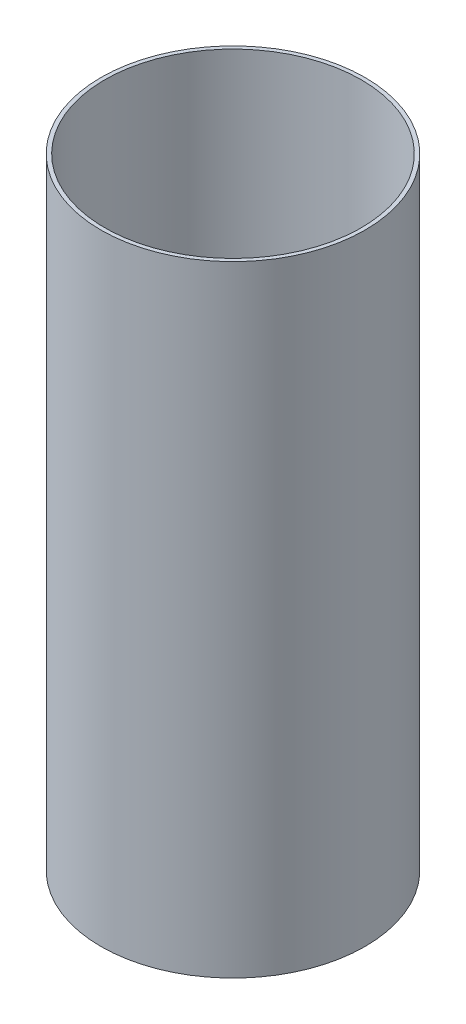
SolidWorks part; units mm, degrees
ref_plane "Front Plane" through (0, 0, 0) normal (0, 0, 1) x (1, 0, 0)
ref_plane "Top Plane" through (0, 0, 0) normal (0, 1, 0) x (1, 0, 0)
ref_plane "Right Plane" through (0, 0, 0) normal (1, 0, 0) x (0, 0, -1)
sketch "Sketch1" plane through (0, 0, 0) normal (0, 1, 0) x (1, 0, 0)
  circle A0 centre (0, 0) radius 31.5
  circle A1 centre (0, 0) radius 32.45
  dimension "D1" = 64.9
  dimension "D2" = 63
extrude "Boss-Extrude1" add sketch "Sketch1" along normal blind 152.4
